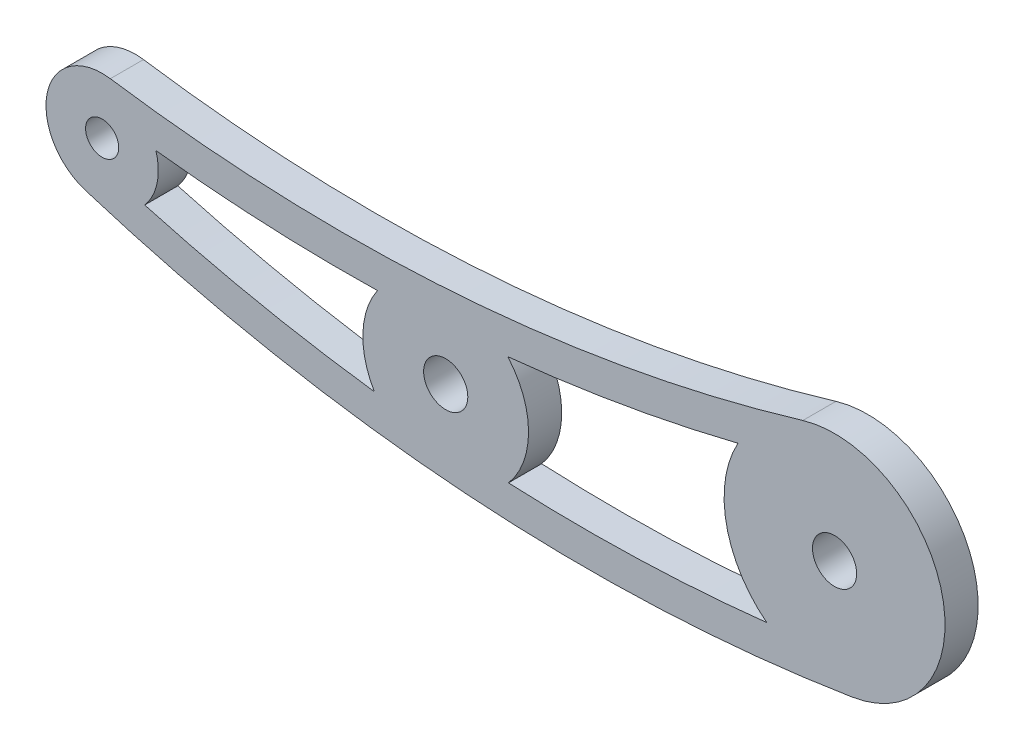
SolidWorks part; units mm, degrees
material "Plain Carbon Steel"
ref_plane "Front Plane" through (0, 0, 0) normal (0, 0, 1) x (1, 0, 0)
ref_plane "Top Plane" through (0, 0, 0) normal (0, 1, 0) x (1, 0, 0)
ref_plane "Right Plane" through (0, 0, 0) normal (1, 0, 0) x (0, 0, -1)
sketch "Sketch1" plane through (0, 0, 0) normal (0, 0, 1) x (1, 0, 0)
  line L0 (0, 0) -> (66.3, 0)
  line L1 (0, -8) -> (66.3, -8)
  line L2 (0, 8) -> (66.3, 8)
  line L3 (0, -5) -> (66.3, -5)
  circle A0 centre (66.3, 0) radius 2
  circle A1 centre (0, 0) radius 1.5
  arc A2 (0, -8) -> (0, 8) centre (0, 0) cw
  arc A3 (66.3, -8) -> (66.3, 8) centre (66.3, 0) ccw
  circle A4 centre (31.1, -3.74) radius 1.5
  circle A5 centre (33.15, 176.6537) radius 184.6537
  circle A6 centre (33.15, 176.6537) radius 174.6537
  circle A7 centre (0, 0) radius 5.0835
  circle A8 centre (66.3, 0) radius 5.0835
  dimension "D2" = 4
  dimension "D1" = 3
extrude "Extrude1" add sketch "Sketch1" along normal blind 3
sketch "Sketch2" plane through (0, 0, 3) normal (0, 0, 1) x (1, 0, 0)
  circle A0 centre (31.1, -3.74) radius 7.5 construction
  arc A1 (67.8926, -9.8724) -> (63.4272, 9.5785) centre (66.3, 0) ccw
  arc A2 (0.742, 5.029) -> (63.4272, 9.5785) centre (21.8615, 148.164) ccw
  arc A3 (0.9376, 4.9963) -> (-2.1931, -4.5861) centre (0, 0) ccw construction
  arc A4 (67.8926, -9.8724) -> (-1.5236, -4.8498) centre (43.8061, 139.438) cw
  arc A6 (0.742, 5.029) -> (-1.5236, -4.8498) centre (0, 0) ccw
  arc M1 (-2.1931, -4.5861) -> (68.4931, -4.5861) centre (33.15, 176.6537) ccw
  arc M2 (68.4931, -4.5861) -> (65.3624, 4.9963) centre (66.3, 0) ccw
  arc M3 (65.3624, 4.9963) -> (0.9376, 4.9963) centre (33.15, 176.6537) cw
  arc M4 (0.9376, 4.9963) -> (-2.1931, -4.5861) centre (0, 0) ccw
  circle M5 centre (31.1, -3.74) radius 1.5
  circle M6 centre (0, 0) radius 1.5
  circle M7 centre (66.3, 0) radius 2
  dimension "D1" = 15
  dimension "D2" = 20
extrude "Boss-Extrude1" add sketch "Sketch2" against normal blind 3 contours M4 M1 M2 M3 M5 M7 M6 | A6 A4 A1 A2 M1 M4 M3 M2
sketch "Sketch3" plane through (0, 0, 3) normal (0, 0, 1) x (1, 0, 0)
  circle A0 centre (66.3, 0) radius 2
  circle A1 centre (31.1, -3.74) radius 2
  arc A4 (3.8522, -3.317) -> (4.8693, 1.4601) centre (0, 0) ccw
  arc A5 (24.9211, 0.511) -> (24.6452, -7.5591) centre (31.1, -3.74) ccw
  arc A6 (57.5597, 4.8587) -> (60.1654, -7.8972) centre (66.3, 0) ccw
  arc A7 (36.7182, 1.2285) -> (57.5597, 4.8587) centre (21.8615, 148.164) ccw
  arc A8 (0.3041, 2.0612) -> (-0.6245, -1.9877) centre (0, 0) ccw
  arc A9 (-0.6245, -1.9877) -> (67.4148, -6.9107) centre (43.8061, 139.438) ccw
  arc A10 (67.4148, -6.9107) -> (64.289, 6.7049) centre (66.3, 0) ccw
  arc A11 (0.3041, 2.0612) -> (64.289, 6.7049) centre (21.8615, 148.164) ccw
  arc A13 (3.8522, -3.317) -> (24.6452, -7.5591) centre (43.8061, 139.438) ccw
  arc A15 (4.8693, 1.4601) -> (24.9211, 0.511) centre (21.8615, 148.164) ccw
  arc A16 (36.7813, -8.6361) -> (60.1654, -7.8972) centre (43.8061, 139.438) ccw
  arc A17 (36.7813, -8.6361) -> (36.7182, 1.2285) centre (31.1, -3.74) ccw
  dimension "D2" = 4
  dimension "D3" = 4
  dimension "D1" = 3
extrude "Cut-Extrude1" cut sketch "Sketch3" against normal blind 5
move or copy body "Body-Move/Copy1" [suppressed] bodies to move or copy 105
move or copy body "Body-Move/Copy2" [suppressed] bodies to move or copy 105
move or copy body "Body-Move/Copy3" [suppressed] bodies to move or copy 105
